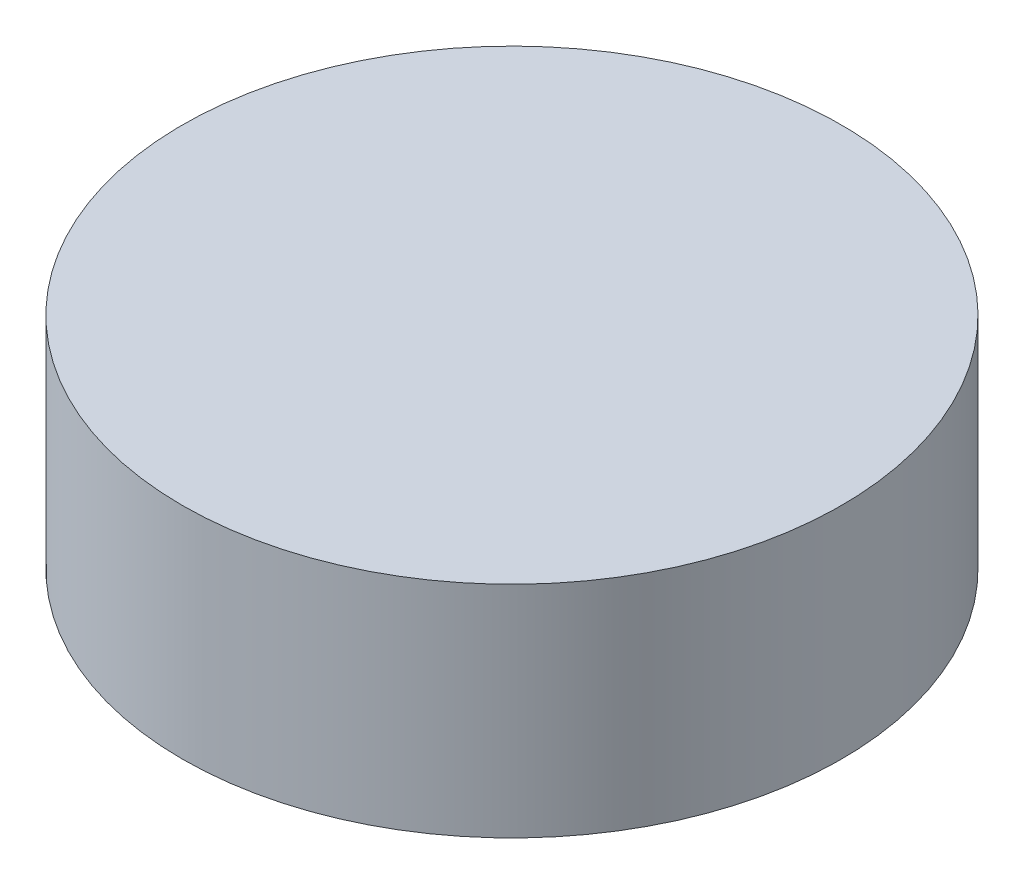
SolidWorks part; units mm, degrees
ref_plane "Front" through (0, 0, 0) normal (0, 0, 1) x (1, 0, 0)
ref_plane "Top" through (0, 0, 0) normal (0, 1, 0) x (1, 0, 0)
ref_plane "Right" through (0, 0, 0) normal (1, 0, 0) x (0, 0, -1)
sketch "Sketch1" plane through (0, 0, 0) normal (0, 1, 0) x (1, 0, 0)
  circle A0 centre (0, 0) radius 3
extrude "Boss-Extrude1" add sketch "Sketch1" along normal blind 2
